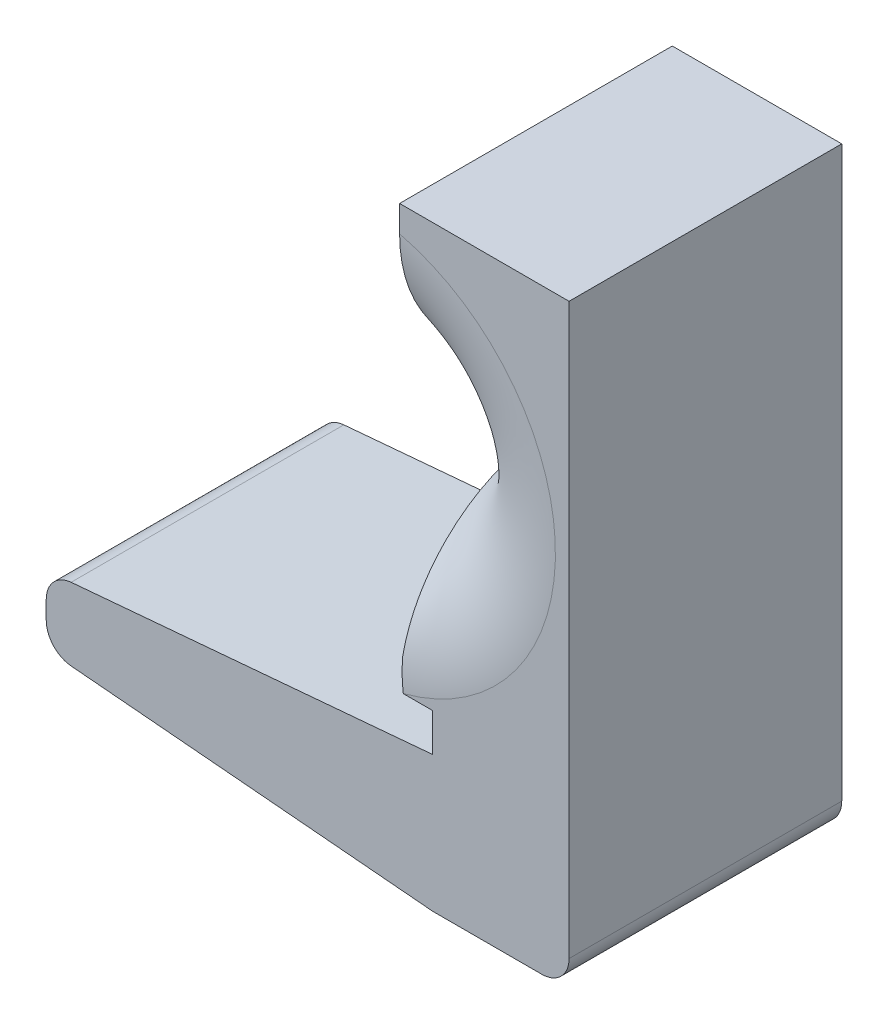
SolidWorks part; units mm, degrees
ref_plane "Front Plane" through (0, 0, 0) normal (0, 0, 1) x (1, 0, 0)
ref_plane "Top Plane" through (0, 0, 0) normal (0, 1, 0) x (1, 0, 0)
ref_plane "Right Plane" through (0, 0, 0) normal (1, 0, 0) x (0, 0, -1)
sketch "finger" plane through (0, 0, 0) normal (0, 0, 1) x (1, 0, 0)
  line L0 (0, 0) -> (5.0161, 13.7815) construction
  line L1 (5.0161, 13.7815) -> (5.0161, 28.518) construction
  line L2 (0, 0) -> (-3.9002, -44.5797)
  line L3 (-3.9002, -44.5797) -> (19.1347, -63.9083)
  line L4 (19.1347, -63.9083) -> (39.9601, -58.3282)
  line L5 (38.7307, -53.74) -> (17.9053, -59.3202)
  line L6 (16.676, -54.732) -> (37.5013, -49.1519)
  line L7 (16.676, -54.732) -> (17.9053, -59.3202)
  line L8 (17.9053, -59.3202) -> (19.1347, -63.9083)
  line L9 (38.7307, -53.74) -> (43.3189, -52.5107) construction
  circle A0 centre (38.7307, -53.74) radius 4.75
  dimension "D3" = 15
  dimension "D4" = 55
  dimension "D5" = 20
  dimension "D6" = 55
  dimension "D7" = 44.75
  dimension "D8" = 30.07
  dimension "D2" = 9.5
  dimension "D1" = 26.31
ref_plane "est_lift_plane" through (38.7307, 0, 0) normal (1, 0, 0) x (0, 0, -1)
sketch "Sketch2" plane through (0, 0, 0) normal (0, 0, 1) x (1, 0, 0)
  line L0 (37.4807, -42.99) -> (37.4807, -39.99) construction
  line L1 (37.4807, -39.99) -> (37.4807, -39.49) construction
  line L2 (37.4807, -42.99) -> (37.4807, -42.89) construction
  line L3 (37.4807, -42.89) -> (37.4807, -42.865) construction
  line L4 (41.0514, -47.99) -> (43.4807, -47.99) construction
  line L5 (37.4807, -44.49) -> (43.4807, -44.49) construction
  line L6 (37.4807, -48.99) -> (43.4807, -48.99) construction
  line L7 (41.0514, -47.99) -> (41.0514, -48.99)
  line L8 (41.0514, -47.99) -> (41.0514, -27.99)
  line L9 (41.0514, -27.99) -> (53.4807, -27.99)
  line L10 (53.4807, -27.99) -> (53.4807, -71.7382)
  line L12 (15.1347, -69.2583) -> (15.1347, -64.2583)
  line L13 (15.1347, -64.2583) -> (43.4807, -61.7783)
  line L14 (43.4807, -61.7783) -> (43.4807, -48.99)
  line L15 (19.1347, -63.9083) -> (19.1347, -69.6082)
  line L16 (15.1347, -66.7583) -> (19.1347, -66.7583)
  line L17 (37.4807, -42.99) -> (37.4807, -42.865) construction
  line L18 (1.0853, 18.3368) -> (13.5146, 18.3368) construction
  line L19 (-25.8903, -11.4233) -> (-21.8903, -11.4233) construction
  line L20 (-25.8903, -13.9233) -> (-25.8903, -8.9233) construction
  line L21 (-2.4854, 5.3476) -> (3.5146, 5.3476) construction
  line L22 (1.0853, 1.8476) -> (3.5146, 1.8476) construction
  line L23 (41.0514, -48.99) -> (41.0514, -58.99) construction
  line L24 (37.4807, -44.49) -> (37.4807, -58.99) construction
  line L25 (37.4807, -44.49) -> (37.4807, -29.99) construction
  line L26 (37.4807, -29.99) -> (37.4807, -27.99) construction
  line L27 (-2.4854, 18.3368) -> (-2.4854, 16.3368) construction
  line L28 (41.0514, -48.99) -> (43.4807, -48.99)
  line L30 (15.1347, -69.2583) -> (43.4807, -71.7382)
  line L34 (43.4807, -71.7382) -> (53.4807, -71.7382)
  line L35 (0, 0) -> (6, 0) construction
  line L37 (3.5707, -3.5) -> (3.5707, -4.5) construction
  line L38 (-23.405, -20.4436) -> (-23.405, -15.4436) construction
  line L39 (-23.405, -17.9436) -> (-19.405, -17.9436) construction
  line L40 (0, 12.8193) -> (0, 10.8193) construction
  circle A0 centre (37.4807, -44.49) radius 5 construction
  circle A1 centre (37.4807, -44.49) radius 4.5 construction
  circle A2 centre (37.4807, -44.49) radius 1.5 construction
  circle A3 centre (37.4807, -44.49) radius 1.6 construction
  circle A4 centre (37.4807, -44.49) radius 1.625 construction
  circle A5 centre (-2.4854, 5.3476) radius 5 construction
  circle A6 centre (-2.4854, 5.3476) radius 4.5 construction
  circle A7 centre (-2.4854, 5.3476) radius 1.625 construction
  circle A9 centre (0, 0) radius 5 construction
  circle A10 centre (-2.4854, 5.3476) radius 1.6 construction
  circle A11 centre (-2.4854, 5.3476) radius 1.5 construction
  circle A12 centre (38.7307, -53.74) radius 4.75 construction
  circle A13 centre (0, 0) radius 4.5 construction
  dimension "D2" = 5
  dimension "D1" = 10
  dimension "D3" = 10
extrude "Boss-Extrude1" add sketch "Sketch2" along normal mid plane 20
sketch "Sketch4" plane through (43.4807, 0, 0) normal (-1, 0, 0) x (0, 0, 1)
  line L0 (0, -31.5595) -> (0, 31.5595) construction
  line L1 (-10, -58.99) -> (-10, -48.99)
  line L2 (-10, -48.99) -> (10, -48.99)
  line L3 (10, -48.99) -> (10, -58.99)
  circle A0 centre (0, -58.99) radius 10 construction
  arc A1 (-10, -58.99) -> (10, -58.99) centre (0, -58.99) cw
  line M4 (-10, -48.99) -> (-10, -61.7783)
  line M6 (10, -61.7783) -> (10, -48.99)
  line M7 (10, -48.99) -> (-10, -48.99)
extrude "Boss-Extrude2" add sketch "Sketch4" along normal up to surface (2.4293 mm away) contours A1 L2 M4 | A1 M7 M6 up to face at (41.0514, -38.49, 0)
ref_plane "roller_plane" through (37.4807, 0, 0) normal (-1, 0, 0) x (0, 0, 1)
sketch "Sketch3" plane through (37.4807, 0, 0) normal (-1, 0, 0) x (0, 0, 1)
  line L0 (0, -31.5595) -> (0, 31.5595) construction
  line L1 (0, 0) -> (0, -44.5797) construction
  line L2 (-10, -44.49) -> (10, -44.49)
  line L3 (-10, -58.99) -> (-10, -27.99) construction
  line L4 (10, -27.99) -> (10, -58.99) construction
  line L5 (-10, -44.49) -> (-10, -29.49)
  line L6 (10, -44.49) -> (10, -29.49)
  circle A0 centre (0, -29.49) radius 10 construction
  arc A1 (-10, -29.49) -> (10, -29.49) centre (0, -29.49) ccw
revolve "Cut-Revolve1" cut sketch "Sketch3" angle 360 about L2
fillet "Fillet2" radius 2 3 edges at (53.4807, -71.7382, 0) (15.1347, -64.2583, 0) (15.1347, -69.2583, 0)
equation "\"depth\"= 9"
equation "\"width\"= 20"
equation "\"distal\"= 26.31"
equation "\"proximal\"= 44.75"
equation "\"medial\"= 30.07"
equation "\"h_offset\"= 0"
equation "\"l_offset\"= 0"
equation "\"D7@finger\" = \"proximal\""
equation "\"D8@finger\" = \"medial\""
equation "\"D1@Boss-Extrude1\"=\"width\""
equation "\"D1@finger\"=\"distal\""
equation "\"D1@Sketch2\"=\"width\"/2"
